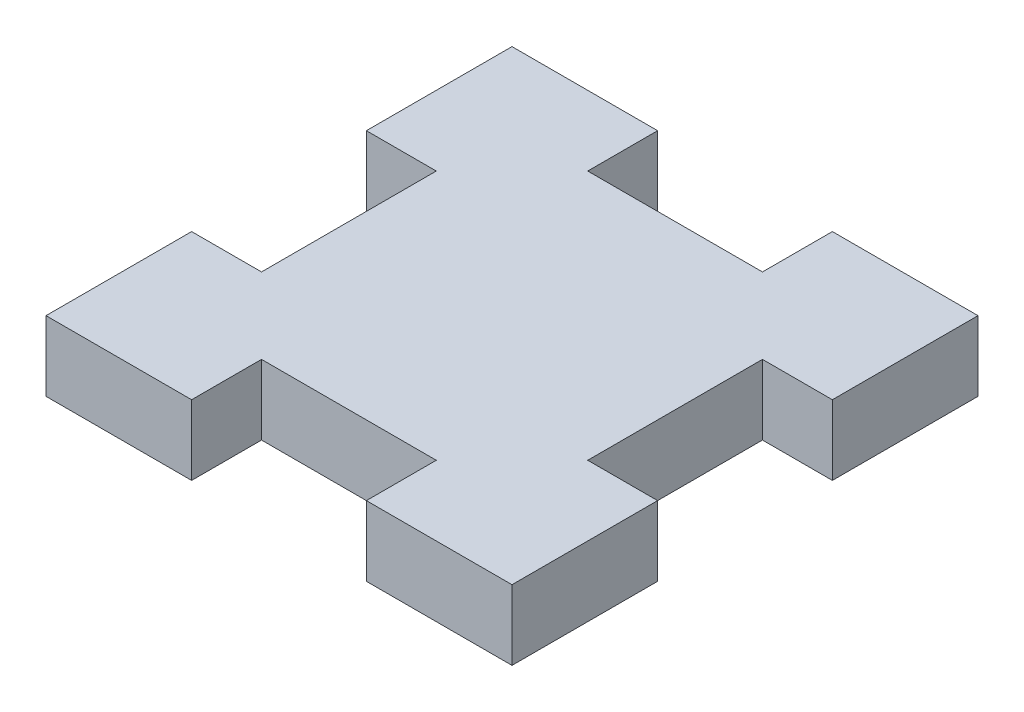
SolidWorks part; units mm, degrees
ref_plane "Alzado" through (0, 0, 0) normal (0, 0, 1) x (1, 0, 0)
ref_plane "Planta" through (0, 0, 0) normal (0, 1, 0) x (1, 0, 0)
ref_plane "Vista lateral" through (0, 0, 0) normal (1, 0, 0) x (0, 0, -1)
sketch "Croquis1" plane through (0, 0, 0) normal (0, 1, 0) x (1, 0, 0)
  line L0 (40, 40) -> (0, 0) construction
  line L1 (0, 0) -> (40, 0)
  line L2 (0, 0) -> (0, 40)
  line L3 (0, 40) -> (40, 40)
  line L4 (40, 0) -> (40, 40)
  line L5 (12.5, 40) -> (27.5, 40)
  line L6 (12.5, 40) -> (12.5, 34)
  line L7 (12.5, 34) -> (27.5, 34)
  line L8 (20, 40) -> (20, 0) construction
  line L9 (0, 20) -> (40, 20) construction
  line L10 (27.5, 40) -> (27.5, 34)
  line L11 (12.5, 0) -> (12.5, 6)
  line L12 (0, 27.5) -> (6, 27.5)
  line L13 (0, 27.5) -> (0, 12.5)
  line L14 (0, 12.5) -> (6, 12.5)
  line L15 (6, 27.5) -> (6, 12.5)
  line L16 (27.5, 6) -> (12.5, 6)
  line L17 (27.5, 0) -> (27.5, 6)
  line L18 (27.5, 0) -> (12.5, 0)
  line L19 (34, 12.5) -> (34, 27.5)
  line L20 (40, 27.5) -> (34, 27.5)
  line L21 (40, 12.5) -> (40, 27.5)
  line L22 (40, 12.5) -> (34, 12.5)
  point P10 (20, 34)
  point P18 (6, 20)
  dimension "D1" = 40
  dimension "D2" = 40
  dimension "D3" = 15
  dimension "D4" = 6
extrude "Saliente-Extruir1" add sketch "Croquis1" along normal blind 6
